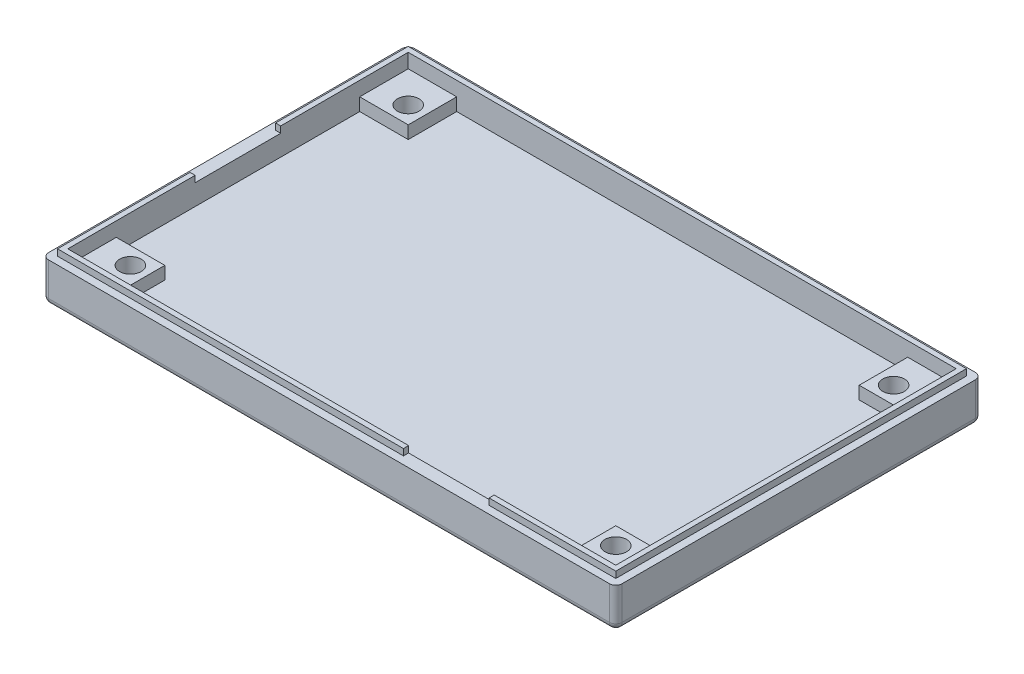
SolidWorks part; units mm, degrees
ref_plane "Front Plane" through (0, 0, 0) normal (0, 0, 1) x (1, 0, 0)
ref_plane "Top Plane" through (0, 0, 0) normal (0, 1, 0) x (1, 0, 0)
ref_plane "Right Plane" through (0, 0, 0) normal (1, 0, 0) x (0, 0, -1)
sketch "Sketch1" plane through (0, 0, 0) normal (0, 1, 0) x (1, 0, 0)
  line L0 (107.95, 66.675) -> (107.95, 0) construction
  line L1 (0, 66.675) -> (107.95, 66.675) construction
  line L2 (0, 0) -> (0, 24.8095) construction
  line L3 (0, 66.675) -> (0, 41.8255) construction
  line L4 (107.95, 0) -> (84.2727, 0) construction
  line L5 (0, 0) -> (67.2567, 0) construction
  line L6 (-0.508, -0.508) -> (-0.508, 24.8095) construction
  line L7 (-0.508, 67.183) -> (108.458, 67.183)
  line L8 (108.458, 67.183) -> (108.458, -0.508)
  line L9 (108.458, -0.508) -> (-0.508, -0.508)
  line L10 (108.458, -0.508) -> (84.2727, -0.508) construction
  line L11 (-0.508, -0.508) -> (-0.508, 67.183)
  line L12 (-0.508, 67.183) -> (-0.508, 41.8255) construction
  line L13 (-0.508, -0.508) -> (67.2567, -0.508) construction
  line L14 (-3.048, 69.723) -> (110.998, 69.723)
  line L15 (110.998, 69.723) -> (110.998, -3.048)
  line L16 (110.998, -3.048) -> (-3.048, -3.048)
  line L17 (-3.048, -3.048) -> (-3.048, 69.723)
  circle A0 centre (5.715, 5.715) radius 2.1526 construction
  circle A1 centre (102.235, 5.715) radius 2.1527 construction
  circle A2 centre (102.235, 60.96) radius 2.1527 construction
  circle A3 centre (5.715, 60.96) radius 2.1526 construction
  dimension "D1" = 0.508
  dimension "D2" = 2.54
extrude "Boss-Extrude1" add sketch "Sketch1" along normal blind 5.3848
sketch "Sketch2" plane through (0, 0, 0) normal (0, -1, 0) x (1, 0, 0)
  line L1 (110.998, -69.723) -> (-3.048, -69.723)
  line L2 (110.998, -69.723) -> (110.998, 3.048)
  line L3 (110.998, 3.048) -> (-3.048, 3.048)
  line L4 (-3.048, -69.723) -> (-3.048, 3.048)
extrude "Boss-Extrude2" add sketch "Sketch2" along normal blind 2.54
sketch "Sketch3" plane through (0, 0, 0) normal (0, 1, 0) x (1, 0, 0)
  line L0 (7.8676, 60.96) -> (7.8676, 72.779) construction
  line L1 (-0.508, 67.183) -> (9.1376, 67.183)
  line L2 (-0.508, 67.183) -> (-0.508, 57.5374)
  line L3 (-0.508, 57.5374) -> (9.1376, 57.5374)
  line L4 (9.1376, 67.183) -> (9.1376, 57.5374)
  line L5 (5.715, 58.8074) -> (-6.8602, 58.8074) construction
  line L6 (53.975, 66.675) -> (53.975, 0) construction
  line L7 (0, 66.675) -> (107.95, 66.675) construction
  line L8 (0, 0) -> (67.2567, 0) construction
  line L9 (107.95, 33.3375) -> (0, 33.3375) construction
  line L10 (107.95, 66.675) -> (107.95, 0) construction
  line L11 (102.235, 58.8074) -> (114.8102, 58.8074) construction
  line L12 (100.0823, 60.96) -> (100.0823, 72.779) construction
  line L13 (98.8123, 67.183) -> (98.8123, 57.5374)
  line L14 (108.458, 57.5374) -> (98.8123, 57.5374)
  line L15 (108.458, 67.183) -> (108.458, 57.5374)
  line L16 (108.458, 67.183) -> (98.8123, 67.183)
  line L17 (100.0823, 5.715) -> (100.0823, -6.104) construction
  line L18 (102.235, 7.8677) -> (114.8102, 7.8677) construction
  line L19 (5.715, 7.8677) -> (-6.8602, 7.8677) construction
  line L20 (7.8676, 5.715) -> (7.8676, -6.104) construction
  line L21 (108.458, -0.508) -> (98.8123, -0.508)
  line L22 (108.458, -0.508) -> (108.458, 9.1377)
  line L23 (108.458, 9.1377) -> (98.8123, 9.1377)
  line L24 (98.8123, -0.508) -> (98.8123, 9.1377)
  line L25 (9.1376, -0.508) -> (9.1376, 9.1377)
  line L26 (-0.508, 9.1377) -> (9.1376, 9.1377)
  line L27 (-0.508, -0.508) -> (-0.508, 9.1377)
  line L28 (-0.508, -0.508) -> (9.1376, -0.508)
  circle A2 centre (5.715, 60.96) radius 2.1526 construction
  dimension "D1" = 1.27
  dimension "D2" = 1.27
extrude "Boss-Extrude3" add sketch "Sketch3" along normal blind 3.81
sketch "Sketch4" plane through (0, 3.81, 0) normal (0, 1, 0) x (1, 0, 0)
  circle A0 centre (5.715, 60.96) radius 2.15
  circle A1 centre (5.715, 5.715) radius 2.15
  circle A2 centre (102.235, 5.715) radius 2.15
  circle A3 centre (102.235, 60.96) radius 2.15
  dimension "D1" = 4.3
extrude "Cut-Extrude1" cut sketch "Sketch4" against normal blind 76.2 and the other way through all
sketch "Sketch5" plane through (0, -2.54, 0) normal (0, -1, 0) x (1, 0, 0)
  circle A0 centre (5.715, -60.96) radius 3.8735
  circle A1 centre (5.715, -5.715) radius 3.8735
  circle A2 centre (102.235, -60.96) radius 3.8735
  circle A3 centre (102.235, -5.715) radius 3.8735
  dimension "D1" = 7.747
extrude "Cut-Extrude2" cut sketch "Sketch5" against normal blind 2.54
sketch "Sketch6" plane through (0, 0, 0) normal (0, 1, 0) x (1, 0, 0)
  line L0 (9.1376, 67.183) -> (98.8123, 67.183)
  line L1 (98.8123, 67.183) -> (98.8123, 57.5374)
  line L2 (98.8123, 57.5374) -> (108.458, 57.5374)
  line L3 (108.458, 57.5374) -> (108.458, 9.1377)
  line L4 (108.458, 9.1377) -> (98.8123, 9.1377)
  line L5 (98.8123, 9.1377) -> (98.8123, -0.508)
  line L6 (98.8123, -0.508) -> (9.1376, -0.508)
  line L7 (9.1376, -0.508) -> (9.1376, 9.1377)
  line L8 (9.1376, 9.1377) -> (-0.508, 9.1377)
  line L9 (-0.508, -0.508) -> (-0.508, 67.183) construction
  line L10 (-0.508, 9.1377) -> (-0.508, 57.5374)
  line L11 (-0.508, 57.5374) -> (9.1376, 57.5374)
  line L12 (9.1376, 57.5374) -> (9.1376, 67.183)
extrude "Boss-Extrude4" add sketch "Sketch6" along normal blind 1.27
sketch "Sketch7" plane through (0, 5.3848, 0) normal (0, 1, 0) x (1, 0, 0)
  line L0 (-0.508, 67.183) -> (108.458, 67.183)
  line L1 (108.458, 67.183) -> (108.458, -0.508)
  line L2 (108.458, -0.508) -> (84.2727, -0.508)
  line L3 (-0.508, -0.508) -> (-0.508, 24.8095)
  line L4 (-1.524, 68.199) -> (109.474, 68.199)
  line L5 (109.474, 68.199) -> (109.474, -1.524)
  line L6 (109.474, -1.524) -> (84.2727, -1.524)
  line L7 (-1.524, -1.524) -> (-1.524, 24.8095)
  line L8 (-1.524, 41.8255) -> (-0.508, 41.8255)
  line L9 (-0.508, 24.8095) -> (-1.524, 24.8095)
  line L10 (-1.524, 41.8255) -> (-1.524, 68.199)
  line L11 (-0.508, 41.8255) -> (-0.508, 67.183)
  line L12 (-1.524, -1.524) -> (-1.524, 68.199) construction
  line L13 (67.2567, -0.508) -> (67.2567, -1.524)
  line L14 (-0.508, -0.508) -> (-0.508, 67.183) construction
  line L15 (84.2727, -0.508) -> (84.2727, -1.524)
  line L16 (67.2567, -0.508) -> (-0.508, -0.508)
  line L17 (67.2567, -1.524) -> (-1.524, -1.524)
  line L18 (108.458, -0.508) -> (-0.508, -0.508) construction
  line L20 (109.474, -1.524) -> (-1.524, -1.524) construction
  dimension "D1" = 1.016
extrude "Boss-Extrude5" add sketch "Sketch7" along normal blind 1.27
fillet "Fillet1" radius 1.27 8 edges at (-3.048, -2.54, -33.3375) (53.975, -2.54, -69.723) (110.998, -2.54, -33.3375) (53.975, -2.54, 3.048) (-3.048, 1.4224, 3.048) (-3.048, 1.4224, -69.723) (110.998, 1.4224, -69.723) (110.998, 1.4224, 3.048)
